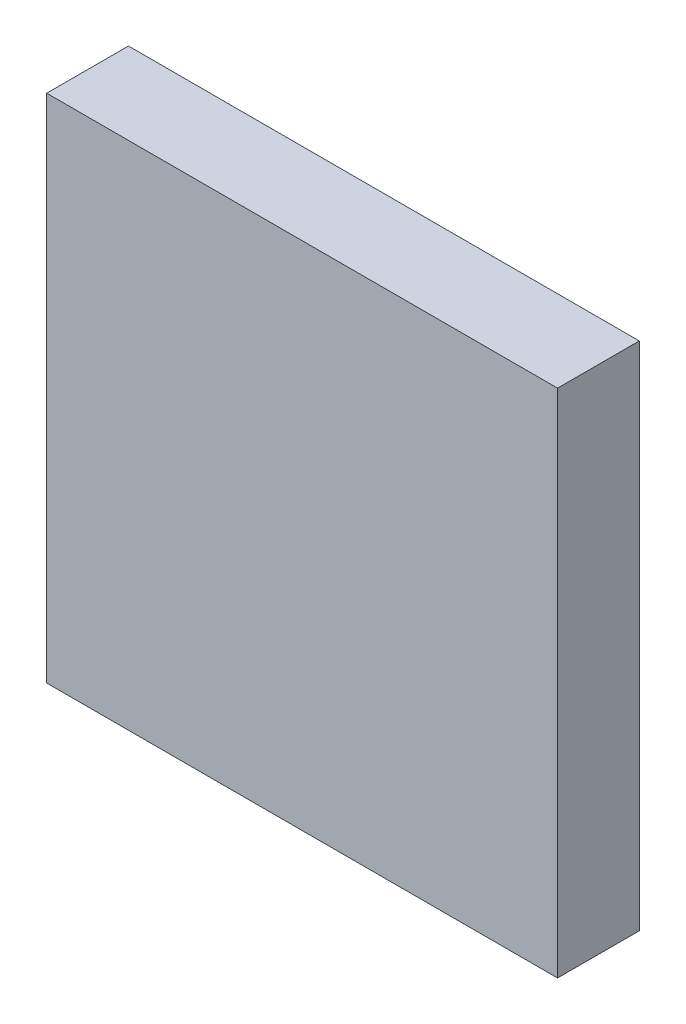
SolidWorks part; units mm, degrees
ref_plane "Front Plane" through (0, 0, 0) normal (0, 0, 1) x (1, 0, 0)
ref_plane "Top Plane" through (0, 0, 0) normal (0, 1, 0) x (1, 0, 0)
ref_plane "Right Plane" through (0, 0, 0) normal (1, 0, 0) x (0, 0, -1)
sketch "草圖1" plane through (0, 0, 0) normal (0, 0, 1) x (1, 0, 0)
  line L0 (-12.5, -12.5) -> (12.5, -12.5)
  line L1 (12.5, -12.5) -> (12.5, 12.5)
  line L2 (12.5, 12.5) -> (-12.5, 12.5)
  line L3 (-12.5, 12.5) -> (-12.5, -12.5)
extrude "填料-伸長1" add sketch "草圖1" along normal blind 4
